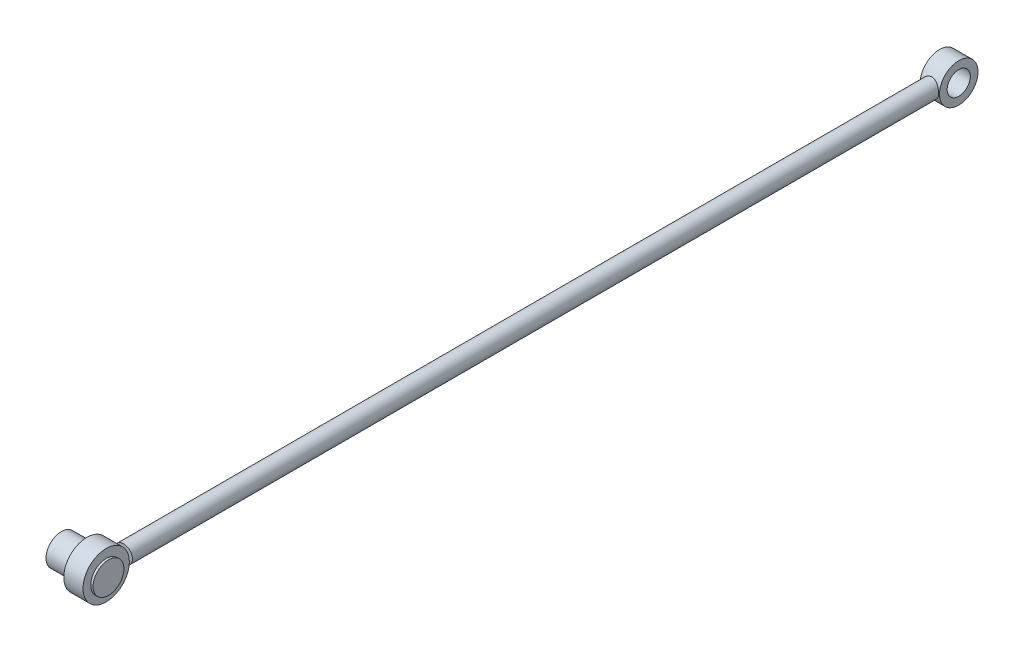
SolidWorks part; units mm, degrees
ref_plane "Front Plane" through (0, 0, 0) normal (0, 0, 1) x (1, 0, 0)
ref_plane "Top Plane" through (0, 0, 0) normal (0, 1, 0) x (1, 0, 0)
ref_plane "Right Plane" through (0, 0, 0) normal (1, 0, 0) x (0, 0, -1)
sketch "Sketch1" plane through (0, 0, 0) normal (0, 0, 1) x (1, 0, 0)
  circle A0 centre (0, 0) radius 1.15
  dimension "D1" = 2.3
extrude "Boss-Extrude1" add sketch "Sketch1" along normal mid plane 105
sketch "Sketch2" plane through (0, 0, 0) normal (0, 1, 0) x (1, 0, 0)
  line L0 (-2.6766, 54.5) -> (1.9371, 54.5) construction
  line L1 (1.15, 52.5) -> (-1.15, 52.5) construction
  line L2 (1.15, 52.5) -> (-1.15, 52.5) construction
  line L4 (-1.25, 53) -> (1.25, 53)
  line L5 (-1.25, 53) -> (-1.25, 52)
  line L6 (-1.25, 52) -> (1.25, 52)
  line L7 (1.25, 53) -> (1.25, 52)
  dimension "D1" = 0.5
  dimension "D2" = 2.5
  dimension "D3" = 1
  dimension "D4" = 1.25
  dimension "D5" = 2.5
revolve "Revolve1" add sketch "Sketch2" angle 360 about L0
sketch "Sketch6" plane through (0, 0, 0) normal (0, 1, 0) x (1, 0, 0)
  line L0 (-1.15, -52.5) -> (1.15, -52.5) construction
  line L1 (-1.25, -53) -> (1.25, -53)
  line L2 (-1.25, -53) -> (-1.25, -56)
  line L3 (-1.25, -56) -> (1.25, -56)
  line L4 (1.25, -53) -> (1.25, -56)
  line L5 (-1.15, -52.5) -> (1.15, -52.5)
  line L7 (-1.25, 57) -> (-1.25, 52) construction
  line L8 (1.25, 52) -> (1.25, 57) construction
  point P6 (0, 0)
  point P7 (0, 0)
  dimension "D1" = 3
  dimension "D2" = 0.5
revolve "Revolve2" add sketch "Sketch6" angle 360 about L3
sketch "Sketch8" plane through (-1.25, 0, 0) normal (-1, 0, 0) x (0, 0, 1)
  circle A0 centre (56, 0) radius 2
  dimension "D1" = 4
extrude "Boss-Extrude3" add sketch "Sketch8" along normal blind 3.3 contours A0
sketch "Sketch12" plane through (1.25, 0, 0) normal (1, 0, 0) x (0, 0, -1)
  circle A0 centre (-56, -0.1281) radius 2
  dimension "D1" = 4
extrude "Boss-Extrude4" add sketch "Sketch12" along normal blind 0.3
sketch "Sketch14" plane through (0, 0, 52.5) normal (0, 0, 1) x (1, 0, 0)
  circle A1 centre (0, 0) radius 1.15
  circle A2 centre (0, 0) radius 1.15
  dimension "D1" = 0
